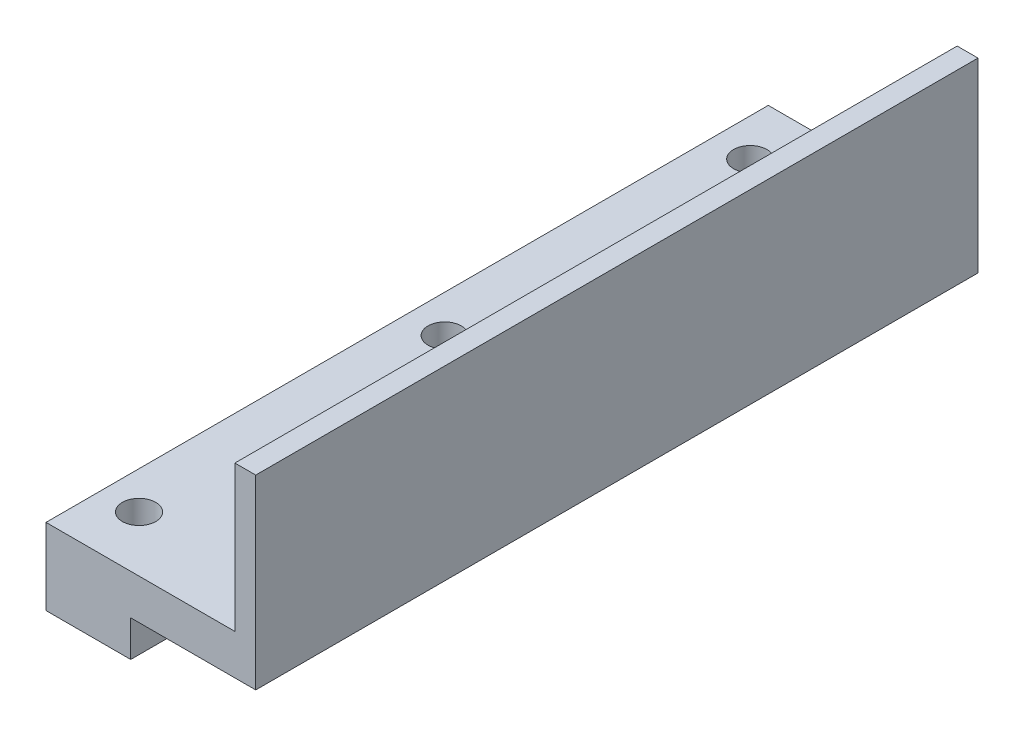
SolidWorks part; units mm, degrees
material "6061-T6 (SS)"
ref_plane "Front Plane" through (0, 0, 0) normal (0, 0, 1) x (1, 0, 0)
ref_plane "Top Plane" through (0, 0, 0) normal (0, 1, 0) x (1, 0, 0)
ref_plane "Right Plane" through (0, 0, 0) normal (1, 0, 0) x (0, 0, -1)
sketch "Sketch1" plane through (0, 0, 0) normal (0, 0, 1) x (1, 0, 0)
  line L4 (0, 0) -> (6.1, 0)
  line L17 (6.1, 2.6) -> (6.1, 0)
  line L21 (6.1, 2.6) -> (13.6, 2.6)
  line L23 (13.6, 5.5) -> (13.6, 2.6)
  line L24 (0, 0) -> (0, 5.5)
  line L25 (13.6, 5.5) -> (0, 5.5)
  dimension "D3" = 6.1
  dimension "D4" = 5.5
  dimension "D6" = 7.5
  dimension "D10" = 2.6
extrude "Boss-Extrude2" add sketch "Sketch1" along normal mid plane 52
sketch "Sketch2" plane through (0, 0, 0) normal (0, 1, 0) x (1, 0, 0)
  line L0 (13.6, 26) -> (0, 26) construction
  line L1 (0, -26) -> (0, 26) construction
  line L2 (0, 0) -> (2.7, 0) construction
  circle A0 centre (2.7, 22) radius 1.2
  circle A1 centre (2.7, 0) radius 1.2
  circle A2 centre (2.7, -22) radius 1.2
  dimension "D1" = 2.4
  dimension "D2" = 2.7
  dimension "D3" = 4
  dimension "D4" = 2.7
extrude "Cut-Extrude2" cut sketch "Sketch2" against normal through all and the other way through all
sketch "Sketch3" plane through (13.6, 0, 0) normal (1, 0, 0) x (0, 0, -1)
  line L0 (-26, 2.6) -> (-26, 5.5) construction
  line L1 (26, 2.6) -> (-26, 2.6)
  line L2 (26, 2.6) -> (26, 16)
  line L3 (26, 16) -> (-26, 16)
  line L4 (-26, 2.6) -> (-26, 16)
  dimension "D1" = 13.4
extrude "Boss-Extrude3" add sketch "Sketch3" along normal blind 1.5
